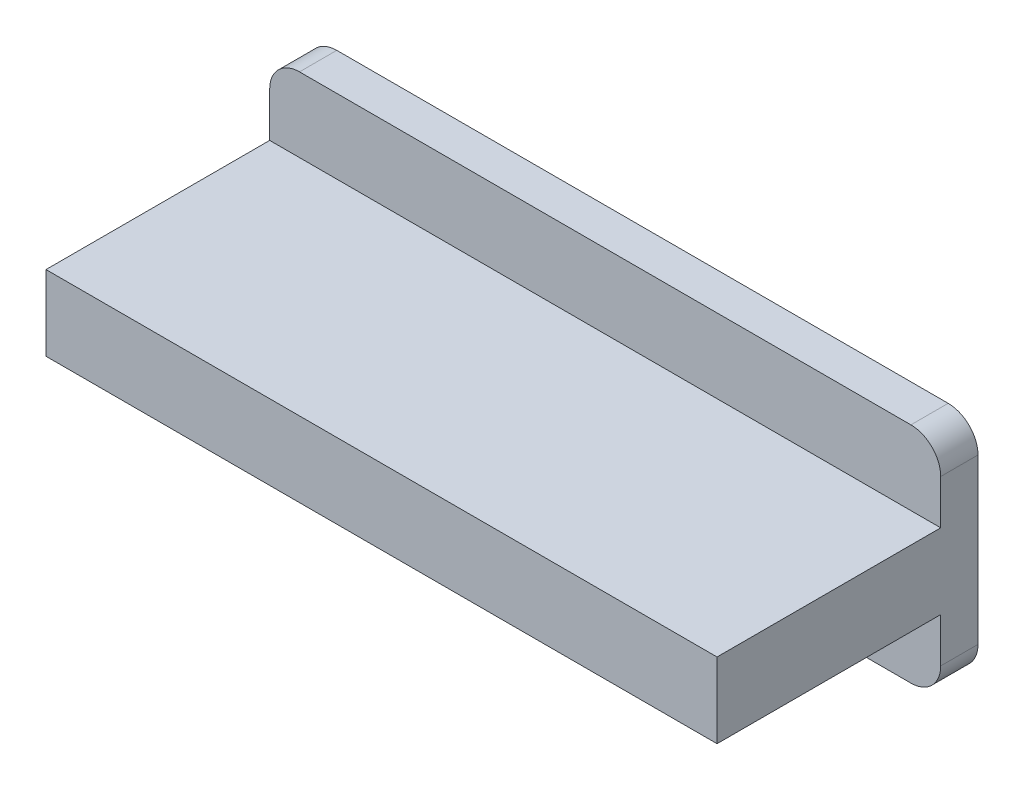
SolidWorks part; units mm, degrees
material "Custom Plastic"
ref_plane "X-Y Datum" through (0, 0, 0) normal (0, 0, 1) x (1, 0, 0)
ref_plane "X-Z Datum" through (0, 0, 0) normal (0, 1, 0) x (1, 0, 0)
ref_plane "Y-Z Datum" through (0, 0, 0) normal (1, 0, 0) x (0, 0, -1)
sketch "Sketch1" plane through (0, 0, 0) normal (0, 0, 1) x (1, 0, 0)
  line L1 (-28.575, -9.525) -> (28.575, -9.525)
  line L2 (-28.575, -9.525) -> (-28.575, 9.525)
  line L3 (-28.575, 9.525) -> (28.575, 9.525)
  line L4 (28.575, -9.525) -> (28.575, 9.525)
  line L5 (-28.575, -9.525) -> (28.575, 9.525) construction
  line L6 (-28.575, 9.525) -> (28.575, -9.525) construction
  point P0 (0, 0)
  dimension "D1" = 19.05
  dimension "D2" = 57.15
extrude "Boss-Extrude1" add sketch "Sketch1" along normal blind 3.175
sketch "Sketch2" plane through (0, 0, 3.175) normal (0, 0, 1) x (1, 0, 0)
  line L0 (28.575, -9.525) -> (28.575, 9.525) construction
  line L1 (-28.575, -3.1994) -> (28.575, -3.1994)
  line L2 (-28.575, -3.1994) -> (-28.575, 3.1994)
  line L3 (-28.575, 3.1994) -> (28.575, 3.1994)
  line L4 (28.575, -3.1994) -> (28.575, 3.1994)
  line L5 (-28.575, -3.1994) -> (28.575, 3.1994) construction
  line L6 (-28.575, 3.1994) -> (28.575, -3.1994) construction
  point P0 (0, 0)
  dimension "D1" = 6.3987
extrude "Boss-Extrude2" add sketch "Sketch2" along normal blind 19.05
fillet "Fillet1" radius 2.54 4 edges at (-28.575, -9.525, 1.5875) (-28.575, 9.525, 1.5875) (28.575, 9.525, 1.5875) (28.575, -9.525, 1.5875)
